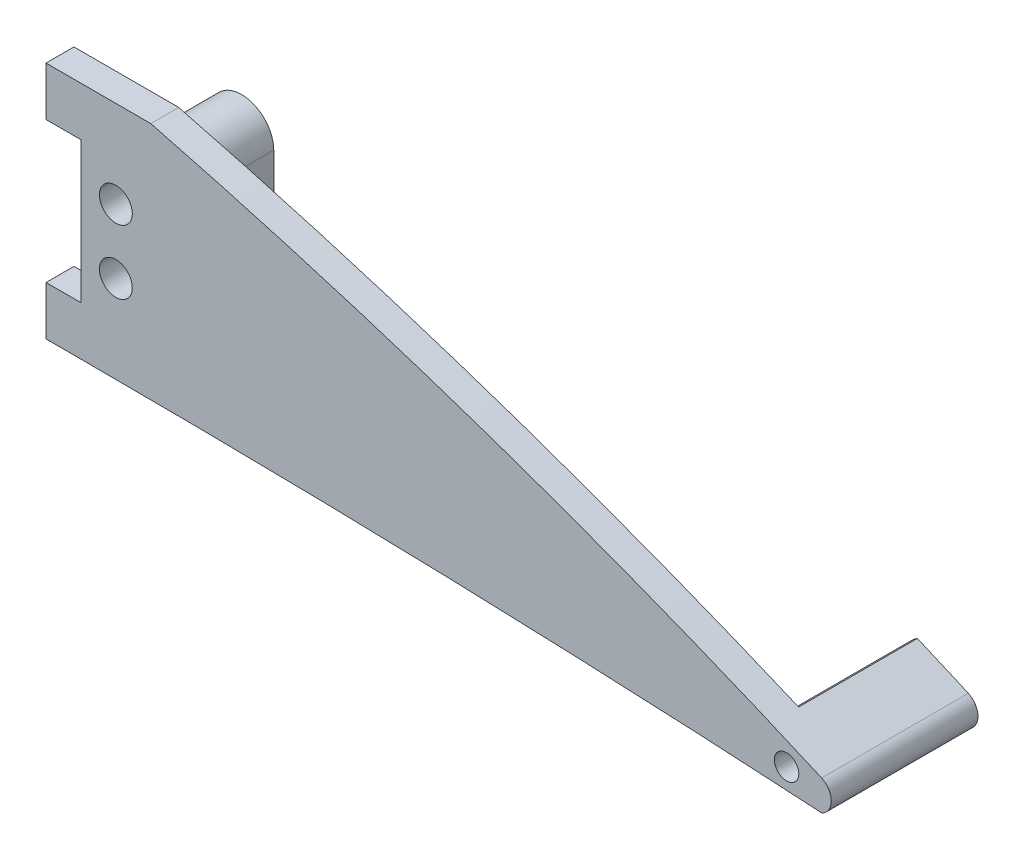
SolidWorks part; units mm, degrees
ref_plane "Płaszczyzna przednia" through (0, 0, 0) normal (0, 0, 1) x (1, 0, 0)
ref_plane "Płaszczyzna górna" through (0, 0, 0) normal (0, 1, 0) x (1, 0, 0)
ref_plane "Płaszczyzna prawa" through (0, 0, 0) normal (1, 0, 0) x (0, 0, -1)
sketch "Szkic2" plane through (0, 0, 0) normal (0, 0, 1) x (1, 0, 0)
  line L9 (15.2, 17.1) -> (15.2, 10.1)
  line L10 (-91.9323, 0) -> (51.5424, 0) construction
  line L11 (0, 24.6927) -> (0, -16.8499) construction
  line L12 (15.2, 17.1) -> (30.2, 17.1)
  line L16 (20.2, 10.1) -> (20.2, -10.1)
  line L19 (15.2, -17.1) -> (19.1974, -17.1)
  line L20 (15.2, 10.1) -> (20.2, 10.1)
  line L21 (15.2, -10.1) -> (20.2, -10.1)
  line L22 (15.2, -10.1) -> (15.2, -17.1)
  circle A5 centre (25.2, 4.6) radius 2.35
  circle A6 centre (25.2, -4.6) radius 2.35
  arc A8 (30.2, 17.1) -> (126.2167, -16.0095) centre (-123.1666, -583.436) cw
  arc A9 (19.1974, -17.1) -> (126.2693, -20.3334) centre (19.1974, -1791.5029) cw
  arc A10 (126.2167, -16.0095) -> (126.2693, -20.3334) centre (125.2, -18.1842) cw
  point P31 (20.2, 0)
  dimension "D8" = 5
  dimension "D12" = 4.7
  dimension "D1" = 34.2
  dimension "D2" = 105
  dimension "D3" = 5
  dimension "D4" = 20.2
  dimension "D5" = 15
  dimension "D6" = 3.9974
  dimension "D7" = 4.6
  dimension "D9" = 7
  dimension "D10" = 7
  dimension "D11" = 20.2
extrude "Dodanie-wyciągnięcie1" add sketch "Szkic2" along normal blind 4
sketch "Szkic3" plane through (0, 0, 4) normal (0, 0, 1) x (1, 0, 0)
  arc A0 (126.2693, -20.3334) -> (19.1974, -17.1) centre (19.1974, -1791.5029) ccw construction
  arc A1 (126.2167, -16.0095) -> (30.2, 17.1) centre (-123.1666, -583.436) ccw construction
  arc A2 (126.2693, -20.3334) -> (126.2167, -16.0095) centre (125.2, -18.1842) ccw construction
  arc A3 (126.2693, -20.3334) -> (117.3332, -19.8158) centre (19.1974, -1791.5029) ccw
  arc A4 (126.2167, -16.0095) -> (118.9224, -12.8594) centre (-123.1666, -583.436) ccw
  arc A5 (126.2693, -20.3334) -> (126.2167, -16.0095) centre (125.2, -18.1842) ccw
  circle A6 centre (121.2, -17.1334) radius 1.75
  arc A7 (117.3332, -19.8158) -> (118.9224, -12.8594) centre (121.606, -17.1322) cw
  dimension "D1" = 3.5
  dimension "D2" = 3.2
  dimension "D3" = 4
extrude "Dodanie-wyciągnięcie2" add sketch "Szkic3" along normal blind 17
sketch "Szkic5" plane through (0, 0, 4) normal (0, 0, 1) x (1, 0, 0)
  line L0 (25.2, -4.6) -> (25.2, 4.6) construction
  line L1 (20.6, -4.6) -> (20.6, 4.6)
  line L2 (29.8, -4.6) -> (29.8, 4.6)
  arc A0 (20.6, -4.6) -> (29.8, -4.6) centre (25.2, -4.6) ccw
  arc A1 (29.8, 4.6) -> (20.6, 4.6) centre (25.2, 4.6) ccw
  point P4 (25.2, 0)
  dimension "D2" = 4.6
  dimension "D1" = 9.2
extrude "Dodanie-wyciągnięcie3" add sketch "Szkic5" along normal blind 14
sketch "Szkic6" plane through (0, 0, 0) normal (0, 0, -1) x (-1, 0, 0)
  circle A0 centre (-25.2, -4.6) radius 2.35 construction
  circle A1 centre (-25.2, 4.6) radius 2.35 construction
  circle A2 centre (-25.2, -4.6) radius 2.35
  circle A3 centre (-25.2, 4.6) radius 2.35
  circle A4 centre (-121.2, -17.1334) radius 1.75 construction
  circle A5 centre (-121.2, -17.1334) radius 1.75
extrude "Wytnij-wyciągnięcie2" cut sketch "Szkic6" against normal through all
mirror "Lustro1" about plane through (125.2, -18.1842, 0) normal (0, 0, -1) of bodies 105
delete or keep bodies "Obiekt-Usuń/zachowaj 1" type delete bodies bodies 105
